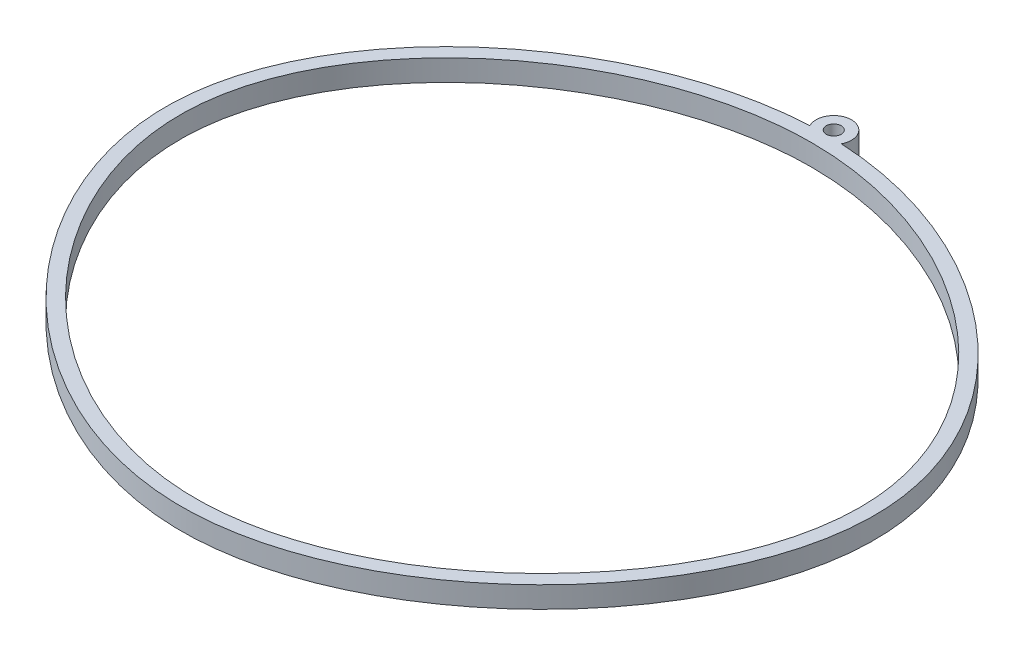
SolidWorks part; units mm, degrees
ref_plane "Front Plane" through (0, 0, 0) normal (0, 0, 1) x (1, 0, 0)
ref_plane "Top Plane" through (0, 0, 0) normal (0, 1, 0) x (1, 0, 0)
ref_plane "Right Plane" through (0, 0, 0) normal (1, 0, 0) x (0, 0, -1)
sketch "Sketch1" plane through (0, 0, 0) normal (0, 1, 0) x (1, 0, 0)
  line L0 (0, 39.087) -> (0, -47.773) construction
  line L1 (-47.857, 0) -> (47.857, 0) construction
  line L2 (0, 41.087) -> (0, -49.773) construction
  line L3 (-49.857, 0) -> (49.857, 0) construction
  circle A0 centre (0, 42.187) radius 1.05
  arc A1 (2.2178, 41.0332) -> (-2.2178, 41.0332) centre (0, 42.187) ccw
  spline S0 degree 3 poles (-71.9153, 0.4397) (0, 57.5401) (71.9153, 0.4397) (0, -72.9653) (-71.9153, 0.4397) (0, 57.5401) (71.9153, 0.4397) knots -0.761263 -0.5 -0.238737 0 0.238737 0.5 0.761263 1 1.238737 1.5 1.761263 only from (0, 39.087) to (0, 39.087)
  spline S1 degree 3 poles (-74.9102, 0.4205) (0, 60.5404) (74.9102, 0.4205) (0, -75.9557) (-74.9102, 0.4205) (0, 60.5404) (74.9102, 0.4205) knots -0.760817 -0.5 -0.239183 0 0.239183 0.5 0.760817 1 1.239183 1.5 1.760817 only from (0, 41.087) to (0, 41.087)
  dimension "D9" = 5
  dimension "D10" = 2.1
  dimension "D1" = 86.86
  dimension "D2" = 95.714
  dimension "D3" = 39.087
  dimension "D4" = 47.857
  dimension "D5" = 90.86
  dimension "D6" = 2
  dimension "D7" = 99.714
  dimension "D8" = 2
  dimension "D11" = 3.1
extrude "Boss-Extrude1" add sketch "Sketch1" along normal blind 3 contours A1 S1 A0 | S1 S0
equation "\"D7@Sketch1\"=\"D2@Sketch1\"+4"
equation "\"D5@Sketch1\"=\"D1@Sketch1\"+4"
equation "\"D3@Sketch1\"=\"D1@Sketch1\"*0.45"
equation "\"D4@Sketch1\"=\"D2@Sketch1\"*0.5"
